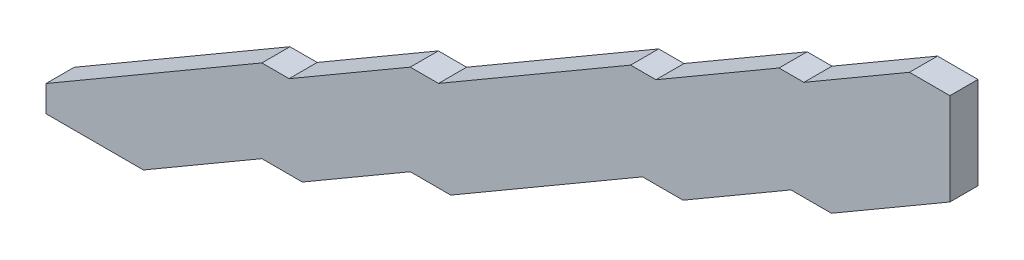
SolidWorks part; units mm, degrees
material "1023 Carbon Steel Sheet (SS)"
ref_plane "Front Plane" through (0, 0, 0) normal (0, 0, 1) x (1, 0, 0)
ref_plane "Top Plane" through (0, 0, 0) normal (0, 1, 0) x (1, 0, 0)
ref_plane "Right Plane" through (0, 0, 0) normal (1, 0, 0) x (0, 0, -1)
sketch "Sketch1" plane through (0, 0, 0) normal (0, 0, 1) x (1, 0, 0)
  line L0 (-156.1443, 57.9329) -> (-155.4744, 57.9329)
  line L1 (-145.8539, 62.4125) -> (-145.8539, 63.3079)
  line L89 (-156.636, 57.9954) -> (-156.636, 57.9329)
  line L90 (-156.636, 57.9329) -> (-156.1443, 57.9329)
  line L91 (-145.8539, 62.4125) -> (-147.2671, 61.5892)
  line L92 (-147.2671, 61.5892) -> (-147.7499, 61.5892)
  line L93 (-147.7499, 61.5892) -> (-149.0373, 60.8392)
  line L94 (-149.0373, 60.8392) -> (-149.5201, 60.8392)
  line L95 (-149.5201, 60.8392) -> (-151.8082, 59.5062)
  line L96 (-151.8082, 59.5062) -> (-152.291, 59.5062)
  line L97 (-152.291, 59.5062) -> (-153.5784, 58.7562)
  line L98 (-153.5784, 58.7562) -> (-154.0612, 58.7562)
  line L99 (-154.0612, 58.7562) -> (-155.4744, 57.9329)
  line L100 (-156.636, 57.9954) -> (-156.636, 58.2454)
  line L101 (-156.636, 58.2454) -> (-154.0612, 59.7454)
  line L102 (-154.0612, 59.7454) -> (-153.7361, 59.7454)
  line L103 (-153.7361, 59.7454) -> (-152.291, 60.5873)
  line L105 (-152.291, 60.5873) -> (-151.9541, 60.5873)
  line L106 (-151.9541, 60.5873) -> (-149.6625, 61.9223)
  line L107 (-149.6625, 61.9223) -> (-149.3604, 61.9223)
  line L108 (-149.3604, 61.9223) -> (-147.8923, 62.7776)
  line L109 (-147.8923, 62.7776) -> (-147.5954, 62.7776)
  line L110 (-147.5954, 62.7776) -> (-146.3366, 63.5109)
  line L111 (-146.3366, 63.5109) -> (-145.8539, 63.5109)
  line L112 (-145.8539, 63.5109) -> (-145.8539, 63.3079)
  dimension "D1" = 0.25
extrude "Boss-Extrude1" add sketch "Sketch1" along normal blind 0.335 contours L112 L111 L110 L109 L108 L107 L106 L105 L103 L102 L101 L100 L89 L90 L0 L99 L98 L97 L96 L95 L94 L93 L92 L91 L1
scale "Scale1" scale about centroid uniform scaling yes scale factor 1000
